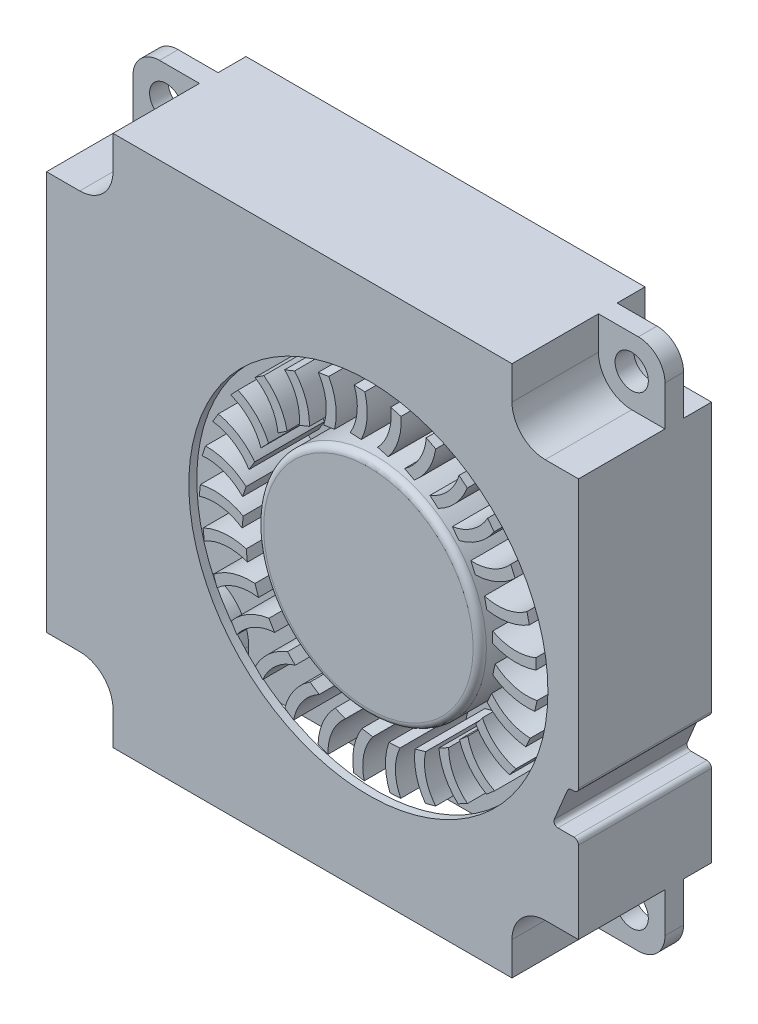
SolidWorks part; units mm, degrees
ref_plane "Front Plane" through (0, 0, 0) normal (0, 0, 1) x (1, 0, 0)
ref_plane "Top Plane" through (0, 0, 0) normal (0, 1, 0) x (1, 0, 0)
ref_plane "Right Plane" through (0, 0, 0) normal (1, 0, 0) x (0, 0, -1)
ref_plane "Plane3" through (0, 0, 25.289) normal (0, 0, 1) x (1, 0, 0)
sketch "Sketch35" plane through (0, 0, 25.289) normal (0, 0, 1) x (1, 0, 0)
  line L0 (41.5884, 7.4054) -> (41.5884, 47.4054)
  line L1 (41.5884, 47.4054) -> (1.5884, 47.4054)
  line L2 (1.5884, 47.4054) -> (1.5884, 7.4054)
  line L3 (1.5884, 7.4054) -> (41.5884, 7.4054)
extrude "Boss-Extrude31" add sketch "Sketch35" against normal blind 10 separate body
sketch "Sketch36" plane through (0, 7.4054, 0) normal (0, -1, 0) x (1, 0, 0)
  line L0 (35.5884, 24.689) -> (7.5884, 24.689)
  line L1 (7.5884, 24.689) -> (7.5884, 16.089)
  line L2 (7.5884, 16.089) -> (35.5884, 16.089)
  line L3 (35.5884, 16.089) -> (35.5884, 24.689)
extrude "Cut-Extrude1" cut sketch "Sketch36" against normal blind 39
ref_plane "Plane4" through (7.5884, 0, 0) normal (1, 0, 0) x (0, 0, -1)
sketch "Sketch41" plane through (7.5884, 0, 0) normal (1, 0, 0) x (0, 0, -1)
  line L0 (-24.689, 46.4054) -> (-24.689, 13.4054)
  line L1 (-24.689, 13.4054) -> (-16.089, 13.4054)
  line L2 (-16.089, 13.4054) -> (-16.089, 46.4054)
  line L3 (-16.089, 46.4054) -> (-24.689, 46.4054)
extrude "Cut-Extrude2" cut sketch "Sketch41" against normal blind 5
sketch "Sketch42" plane through (35.5884, 0, 0) normal (-1, 0, 0) x (0, 0, 1)
  line L0 (24.689, 13.4054) -> (24.689, 46.4054)
  line L1 (24.689, 46.4054) -> (16.089, 46.4054)
  line L2 (16.089, 46.4054) -> (16.089, 13.4054)
  line L3 (16.089, 13.4054) -> (24.689, 13.4054)
extrude "Cut-Extrude3" cut sketch "Sketch42" against normal blind 5
ref_plane "Plane5" through (0, 0, 24.689) normal (0, 0, -1) x (-1, 0, 0)
sketch "Sketch48" plane through (0, 0, 24.689) normal (0, 0, -1) x (-1, 0, 0)
  line L0 (-40.5884, 17.9054) -> (-40.5884, 22.825)
  line L1 (-39.8384, 22.1054) -> (-38.8384, 19.7054)
  line L2 (-40.0384, 17.9054) -> (-40.5884, 17.9054)
  arc A0 (-40.5884, 22.825) -> (-39.8384, 22.1054) centre (-41.0384, 21.6054) cw
  arc A1 (-38.8384, 19.7054) -> (-40.0384, 17.9054) centre (-40.0384, 19.2054) cw
extrude "Boss-Extrude32" add sketch "Sketch48" along normal blind 8.6
sketch "Sketch49" plane through (0, 0, 15.289) normal (0, 0, -1) x (-1, 0, 0)
  line L0 (-41.5884, 18.9054) -> (-40.0384, 18.9054)
  line L1 (-39.7615, 19.3207) -> (-40.8384, 21.9054)
  line L2 (-40.8384, 21.9054) -> (-41.5884, 21.9054)
  line L3 (-41.5884, 21.9054) -> (-41.5884, 18.9054)
  arc A0 (-40.0384, 18.9054) -> (-39.7615, 19.3207) centre (-40.0384, 19.2054) ccw
extrude "Cut-Extrude4" cut sketch "Sketch49" against normal through all
sketch "Sketch50" plane through (0, 0, 24.689) normal (0, 0, -1) x (-1, 0, 0)
  line L0 (-40.5884, 41.4054) -> (-40.5884, 46.4054)
  line L1 (-40.5884, 46.4054) -> (-35.5884, 46.4054)
  line L2 (-35.5884, 46.4054) -> (-35.5884, 41.4054)
  line L3 (-35.5884, 41.4054) -> (-40.5884, 41.4054)
extrude "Boss-Extrude33" add sketch "Sketch50" along normal blind 8.6
sketch "Sketch51" plane through (0, 0, 24.689) normal (0, 0, -1) x (-1, 0, 0)
  line L0 (-7.5884, 46.4054) -> (-2.5884, 46.4054)
  line L1 (-2.5884, 46.4054) -> (-2.5884, 41.4054)
  line L2 (-2.5884, 41.4054) -> (-7.5884, 41.4054)
  line L3 (-7.5884, 41.4054) -> (-7.5884, 46.4054)
extrude "Boss-Extrude34" add sketch "Sketch51" along normal blind 8.6
sketch "Sketch52" plane through (0, 0, 25.289) normal (0, 0, 1) x (1, 0, 0)
  line L0 (6.5884, 7.4054) -> (6.5884, 12.4054)
  line L1 (6.5884, 12.4054) -> (1.5884, 12.4054)
  line L2 (1.5884, 12.4054) -> (1.5884, 7.4054)
  line L3 (1.5884, 7.4054) -> (6.5884, 7.4054)
extrude "Cut-Extrude5" cut sketch "Sketch52" against normal blind 6.5
sketch "Sketch53" plane through (0, 0, 25.289) normal (0, 0, 1) x (1, 0, 0)
  line L0 (1.5884, 42.4054) -> (6.5884, 42.4054)
  line L1 (6.5884, 42.4054) -> (6.5884, 47.4054)
  line L2 (6.5884, 47.4054) -> (1.5884, 47.4054)
  line L3 (1.5884, 47.4054) -> (1.5884, 42.4054)
extrude "Cut-Extrude6" cut sketch "Sketch53" against normal blind 6.5
sketch "Sketch54" plane through (0, 0, 25.289) normal (0, 0, 1) x (1, 0, 0)
  line L0 (41.5884, 12.4054) -> (36.5884, 12.4054)
  line L1 (36.5884, 12.4054) -> (36.5884, 7.4054)
  line L2 (36.5884, 7.4054) -> (41.5884, 7.4054)
  line L3 (41.5884, 7.4054) -> (41.5884, 12.4054)
extrude "Cut-Extrude7" cut sketch "Sketch54" against normal blind 6.5
sketch "Sketch55" plane through (0, 0, 25.289) normal (0, 0, 1) x (1, 0, 0)
  line L0 (36.5884, 47.4054) -> (36.5884, 42.4054)
  line L1 (36.5884, 42.4054) -> (41.5884, 42.4054)
  line L2 (41.5884, 42.4054) -> (41.5884, 47.4054)
  line L3 (41.5884, 47.4054) -> (36.5884, 47.4054)
extrude "Cut-Extrude8" cut sketch "Sketch55" against normal blind 6.5
sketch "Sketch56" plane through (0, 0, 15.289) normal (0, 0, -1) x (-1, 0, 0)
  line L0 (-41.5884, 42.4054) -> (-36.5884, 42.4054)
  line L1 (-36.5884, 42.4054) -> (-36.5884, 47.4054)
  line L2 (-36.5884, 47.4054) -> (-41.5884, 47.4054)
  line L3 (-41.5884, 47.4054) -> (-41.5884, 42.4054)
extrude "Cut-Extrude9" cut sketch "Sketch56" against normal blind 2.1
sketch "Sketch57" plane through (0, 0, 15.289) normal (0, 0, -1) x (-1, 0, 0)
  line L0 (-36.5884, 7.4054) -> (-36.5884, 12.4054)
  line L1 (-36.5884, 12.4054) -> (-41.5884, 12.4054)
  line L2 (-41.5884, 12.4054) -> (-41.5884, 7.4054)
  line L3 (-41.5884, 7.4054) -> (-36.5884, 7.4054)
extrude "Cut-Extrude10" cut sketch "Sketch57" against normal blind 2.1
sketch "Sketch58" plane through (0, 0, 15.289) normal (0, 0, -1) x (-1, 0, 0)
  line L0 (-6.5884, 42.4054) -> (-1.5884, 42.4054)
  line L1 (-1.5884, 42.4054) -> (-1.5884, 47.4054)
  line L2 (-1.5884, 47.4054) -> (-6.5884, 47.4054)
  line L3 (-6.5884, 47.4054) -> (-6.5884, 42.4054)
extrude "Cut-Extrude11" cut sketch "Sketch58" against normal blind 2.1
sketch "Sketch59" plane through (0, 0, 15.289) normal (0, 0, -1) x (-1, 0, 0)
  line L0 (-6.5884, 12.4054) -> (-6.5884, 7.4054)
  line L1 (-6.5884, 7.4054) -> (-1.5884, 7.4054)
  line L2 (-1.5884, 7.4054) -> (-1.5884, 12.4054)
  line L3 (-1.5884, 12.4054) -> (-6.5884, 12.4054)
extrude "Cut-Extrude12" cut sketch "Sketch59" against normal blind 2.1
hole_wizard "Ø2.5 (2.5) Diameter Hole1" positions "Sketch61" profile "Sketch60" hole size "Ø2.5" standard "ANSI Metric"
sketch "Sketch61" plane through (0, 0, 18.789) normal (0, 0, 1) x (1, 0, 0)
  point P0 (4.0884, 44.9054)
  point P1 (39.0884, 9.9054)
sketch "Sketch60" plane through (4.0884, 44.9054, 18.789) normal (1, 0, 0) x (0, -1, 0)
  line L0 (0, 0) -> (0, 3.5)
  line L1 (0, 3.5) -> (1.25, 3.5)
  line L2 (1.25, 3.5) -> (1.25, 0)
  line L5 (1.25, 0) -> (0, 0)
  line L10 (0, 3.5) -> (-1.25, 3.5) construction
  line L11 (0, -6.35) -> (0, 107.95) construction
  dimension "Hole Dia." = 2.5
  dimension "Hole Depth" = 3.5
  dimension "Drill Angle" = 180
hole_wizard "M24 Clearance Hole1" positions "Sketch63" profile "Sketch62" hole size "M24" standard "ANSI Metric"
sketch "Sketch63" plane through (0, 0, 25.289) normal (0, 0, 1) x (1, 0, 0)
  point P0 (25.7884, 27.4054)
sketch "Sketch62" plane through (25.7884, 27.4054, 25.289) normal (1, 0, 0) x (0, -1, 0)
  line L0 (0, 0) -> (0, 0.6)
  line L1 (0, 0.6) -> (13.5, 0.6)
  line L2 (13.5, 0.6) -> (13.5, 0)
  line L5 (13.5, 0) -> (0, 0)
  line L11 (0, -6.35) -> (0, 107.95) construction
  dimension "Thru Hole Dia." = 27
  dimension "Thru Hole Depth" = 0.6
hole_wizard "Ø2.5 (2.5) Diameter Hole2" positions "Sketch65" profile "Sketch64" hole size "Ø2.5" standard "ANSI Metric"
sketch "Sketch65" plane through (0, 0, 17.389) normal (0, 0, -1) x (-1, 0, 0)
  point P0 (-4.0884, 9.9054)
  point P1 (-39.0884, 44.9054)
sketch "Sketch64" plane through (4.0884, 9.9054, 17.389) normal (1, 0, 0) x (0, 1, 0)
  line L0 (0, 0) -> (0, 7.9)
  line L1 (0, 7.9) -> (1.25, 7.9)
  line L2 (1.25, 7.9) -> (1.25, 0)
  line L5 (1.25, 0) -> (0, 0)
  line L10 (0, 7.9) -> (-1.25, 7.9) construction
  line L11 (0, -6.35) -> (0, 107.95) construction
  dimension "Hole Dia." = 2.5
  dimension "Hole Depth" = 7.9
  dimension "Drill Angle" = 180
fillet "Fillet2" radius 0.35 3 edges at (41.5884, 18.9054, 20.289) (40.8384, 21.9054, 20.289) (41.5884, 21.9054, 20.289)
fillet "Fillet3" radius 2 4 edges at (1.5884, 47.4054, 18.089) (41.5884, 47.4054, 18.089) (1.5884, 7.4054, 18.089) (41.5884, 7.4054, 18.089)
fillet "Fillet4" radius 2.5 8 edges at (6.5884, 12.4054, 22.039) (36.5884, 12.4054, 16.339) (36.5884, 42.4054, 16.339) (6.5884, 12.4054, 16.339) (6.5884, 42.4054, 16.339) (36.5884, 12.4054, 22.039) (6.5884, 42.4054, 22.039) (36.5884, 42.4054, 22.039)
fillet "Fillet5" radius 3.5 4 edges at (7.5884, 41.4054, 20.389) (7.5884, 13.4054, 20.389) (35.5884, 13.4054, 20.389) (35.5884, 41.4054, 20.389)
ref_plane "Plane6" through (0, 0, 20.039) normal (0, 0, 1) x (1, 0, 0)
sketch "Sketch72" plane through (0, 0, 20.039) normal (0, 0, 1) x (1, 0, 0)
  line L0 (28.2453, 39.8011) -> (27.4688, 40.0157)
  line L1 (25.5232, 40.0394) -> (24.7186, 40.0821)
  line L2 (22.8134, 39.687) -> (22.0185, 39.5558)
  line L3 (20.2428, 38.7604) -> (19.4946, 38.4613)
  line L4 (17.9314, 37.3028) -> (17.2651, 36.8499)
  line L5 (15.9875, 35.3824) -> (15.4341, 34.7968)
  line L6 (14.5018, 33.089) -> (14.0872, 32.3981)
  line L7 (13.5439, 30.5298) -> (13.2875, 29.766)
  line L8 (13.1585, 27.8245) -> (13.0723, 27.0235)
  line L9 (13.3636, 25.0997) -> (13.4517, 24.2988)
  line L10 (14.1498, 22.4826) -> (14.4079, 21.7194)
  line L11 (15.4801, 20.0958) -> (15.8963, 19.4059)
  line L12 (17.2925, 18.0507) -> (17.8472, 17.4664)
  line L13 (19.5021, 16.443) -> (20.1694, 15.9916)
  line L14 (22.0056, 15.3479) -> (22.7544, 15.0506)
  line L15 (24.686, 14.8167) -> (25.4813, 14.6872)
  line L16 (27.418, 14.874) -> (28.2225, 14.9185)
  line L17 (30.0738, 15.5173) -> (30.8499, 15.7337)
  line L18 (32.5292, 16.7165) -> (33.2406, 17.0947)
  line L19 (34.6694, 18.4154) -> (35.2828, 18.9377)
  line L20 (36.3943, 20.5348) -> (36.8812, 21.1767)
  line L21 (37.6233, 22.9754) -> (37.9608, 23.707)
  line L22 (38.2989, 25.6231) -> (38.4712, 26.4102)
  line L23 (38.3896, 28.3542) -> (38.3887, 29.1599)
  line L24 (37.891, 31.0409) -> (37.7169, 31.8275)
  line L25 (36.8265, 33.5576) -> (36.4874, 34.2884)
  line L26 (35.2459, 35.7866) -> (34.7576, 36.4275)
  line L27 (33.2231, 37.6237) -> (32.6084, 38.1447)
  line L28 (30.8526, 38.9831) -> (30.1403, 39.3597)
  arc A0 (29.3247, 37.2919) -> (27.8844, 37.694) centre (25.7884, 27.4054) ccw
  arc A1 (27.8844, 37.694) -> (28.2453, 39.8011) centre (23.7564, 39.4856) ccw
  arc A2 (27.4688, 40.0157) -> (27.1167, 37.821) centre (23.7564, 39.4856) cw
  arc A3 (27.1167, 37.821) -> (25.6236, 37.9041) centre (25.7884, 27.4054) ccw
  arc A4 (25.6236, 37.9041) -> (25.5232, 40.0394) centre (21.207, 38.7664) ccw
  arc A5 (24.7186, 40.0821) -> (24.8466, 37.863) centre (21.207, 38.7664) cw
  arc A6 (24.8466, 37.863) -> (23.3705, 37.6232) centre (25.7884, 27.4054) ccw
  arc A7 (23.3705, 37.6232) -> (22.8134, 39.687) centre (18.8718, 37.5159) ccw
  arc A8 (22.0185, 39.5558) -> (22.6205, 37.4161) centre (18.8718, 37.5159) cw
  arc A9 (22.6205, 37.4161) -> (21.2305, 36.8645) centre (25.7884, 27.4054) ccw
  arc A10 (21.2305, 36.8645) -> (20.2428, 38.7604) centre (16.8601, 35.7927) ccw
  arc A11 (19.4946, 38.4613) -> (20.5425, 36.501) centre (16.8601, 35.7927) cw
  arc A12 (20.5425, 36.501) -> (19.3037, 35.6636) centre (25.7884, 27.4054) ccw
  arc A13 (19.3037, 35.6636) -> (17.9314, 37.3028) centre (15.2658, 33.6773) ccw
  arc A14 (17.2651, 36.8499) -> (18.7099, 35.1607) centre (15.2658, 33.6773) cw
  arc A15 (18.7099, 35.1607) -> (17.68, 34.0765) centre (25.7884, 27.4054) ccw
  arc A16 (17.68, 34.0765) -> (15.9875, 35.3824) centre (14.1635, 31.2686) ccw
  arc A17 (15.4341, 34.7968) -> (17.2082, 33.4577) centre (14.1635, 31.2686) cw
  arc A18 (17.2082, 33.4577) -> (16.4355, 32.1775) centre (25.7884, 27.4054) ccw
  arc A19 (16.4355, 32.1775) -> (14.5018, 33.089) centre (13.6048, 28.6793) ccw
  arc A20 (14.0872, 32.3981) -> (16.1077, 31.4717) centre (13.6048, 28.6793) cw
  arc A21 (16.1077, 31.4717) -> (15.6283, 30.0553) centre (25.7884, 27.4054) ccw
  arc A22 (15.6283, 30.0553) -> (13.5439, 30.5298) centre (13.6158, 26.0304) ccw
  arc A23 (13.2875, 29.766) -> (15.4599, 29.2956) centre (13.6158, 26.0304) cw
  arc A24 (15.4599, 29.2956) -> (15.2961, 27.8092) centre (25.7884, 27.4054) ccw
  arc A25 (15.2961, 27.8092) -> (13.1585, 27.8245) centre (14.196, 23.4458) ccw
  arc A26 (13.0723, 27.0235) -> (15.295, 27.0311) centre (14.196, 23.4458) cw
  arc A27 (15.295, 27.0311) -> (15.4546, 25.5443) centre (25.7884, 27.4054) ccw
  arc A28 (15.4546, 25.5443) -> (13.3636, 25.0997) centre (15.3182, 21.0463) ccw
  arc A29 (13.4517, 24.2988) -> (15.6208, 24.7841) centre (15.3182, 21.0463) cw
  arc A30 (15.6208, 24.7841) -> (16.0963, 23.3663) centre (25.7884, 27.4054) ccw
  arc A31 (16.0963, 23.3663) -> (14.1498, 22.4826) centre (16.93, 18.9442) ccw
  arc A32 (14.4079, 21.7194) -> (16.422, 22.6596) centre (16.93, 18.9442) cw
  arc A33 (16.422, 22.6596) -> (17.1912, 21.3772) centre (25.7884, 27.4054) ccw
  arc A34 (17.1912, 21.3772) -> (15.4801, 20.0958) centre (18.956, 17.2377) ccw
  arc A35 (15.8963, 19.4059) -> (17.6612, 20.7571) centre (18.956, 17.2377) cw
  arc A36 (17.6612, 20.7571) -> (18.688, 19.67) centre (25.7884, 27.4054) ccw
  arc A37 (18.688, 19.67) -> (17.2925, 18.0507) centre (21.3014, 16.0067) ccw
  arc A38 (17.8472, 17.4664) -> (19.2804, 19.1654) centre (21.3014, 16.0067) cw
  arc A39 (19.2804, 19.1654) -> (20.5169, 18.3245) centre (25.7884, 27.4054) ccw
  arc A40 (20.5169, 18.3245) -> (19.5021, 16.443) centre (23.8567, 15.3086) ccw
  arc A41 (20.1694, 15.9916) -> (21.2039, 17.9591) centre (23.8567, 15.3086) cw
  arc A42 (21.2039, 17.9591) -> (22.5923, 17.4036) centre (25.7884, 27.4054) ccw
  arc A43 (22.5923, 17.4036) -> (22.0056, 15.3479) centre (26.5023, 15.1762) ccw
  arc A44 (22.7544, 15.0506) -> (23.3417, 17.1944) centre (26.5023, 15.1762) cw
  arc A45 (23.3417, 17.1944) -> (24.8171, 16.9504) centre (25.7884, 27.4054) ccw
  arc A46 (24.8171, 16.9504) -> (24.686, 14.8167) centre (29.1145, 15.6156) ccw
  arc A47 (25.4813, 14.6872) -> (25.594, 16.9072) centre (29.1145, 15.6156) cw
  arc A48 (25.594, 16.9072) -> (27.0873, 16.986) centre (25.7884, 27.4054) ccw
  arc A49 (27.0873, 16.986) -> (27.418, 14.874) centre (31.5712, 16.6062) ccw
  arc A50 (28.2225, 14.9185) -> (27.8553, 17.1108) centre (31.5712, 16.6062) cw
  arc A51 (27.8553, 17.1108) -> (29.2968, 17.5088) centre (25.7884, 27.4054) ccw
  arc A52 (29.2968, 17.5088) -> (30.0738, 15.5173) centre (33.7575, 18.1019) ccw
  arc A53 (30.8499, 15.7337) -> (30.02, 17.7958) centre (33.7575, 18.1019) cw
  arc A54 (30.02, 17.7958) -> (31.3422, 18.4944) centre (25.7884, 27.4054) ccw
  arc A55 (31.3422, 18.4944) -> (32.5292, 16.7165) centre (35.5712, 20.0325) ccw
  arc A56 (33.2406, 17.0947) -> (31.9869, 18.9302) centre (35.5712, 20.0325) cw
  arc A57 (31.9869, 18.9302) -> (33.128, 19.8967) centre (25.7884, 27.4054) ccw
  arc A58 (33.128, 19.8967) -> (34.6694, 18.4154) centre (36.9274, 22.3079) ccw
  arc A59 (35.2828, 18.9377) -> (33.6639, 20.4608) centre (36.9274, 22.3079) cw
  arc A60 (33.6639, 20.4608) -> (34.5705, 21.65) centre (25.7884, 27.4054) ccw
  arc A61 (34.5705, 21.65) -> (36.3943, 20.5348) centre (37.7628, 24.8216) ccw
  arc A62 (36.8812, 21.1767) -> (34.9726, 22.3162) centre (37.7628, 24.8216) cw
  arc A63 (34.9726, 22.3162) -> (35.6024, 23.6724) centre (25.7884, 27.4054) ccw
  arc A64 (35.6024, 23.6724) -> (37.6233, 22.9754) centre (38.0383, 27.4562) ccw
  arc A65 (37.9608, 23.707) -> (35.8519, 24.4095) centre (38.0383, 27.4562) cw
  arc A66 (35.8519, 24.4095) -> (36.1754, 25.8695) centre (25.7884, 27.4054) ccw
  arc A67 (36.1754, 25.8695) -> (38.2989, 25.6231) centre (37.7409, 30.0884) ccw
  arc A68 (38.4712, 26.4102) -> (36.2607, 26.6429) centre (37.7409, 30.0884) cw
  arc A69 (36.2607, 26.6429) -> (36.2628, 28.1383) centre (25.7884, 27.4054) ccw
  arc A70 (36.2628, 28.1383) -> (38.3896, 28.3542) centre (36.8847, 32.5951) ccw
  arc A71 (38.3887, 29.1599) -> (36.1797, 28.9119) centre (36.8847, 32.5951) cw
  arc A72 (36.1797, 28.9119) -> (35.8603, 30.3728) centre (25.7884, 27.4054) ccw
  arc A73 (35.8603, 30.3728) -> (37.891, 31.0409) centre (35.5097, 34.8591) ccw
  arc A74 (37.7169, 31.8275) -> (35.6129, 31.1106) centre (35.5097, 34.8591) cw
  arc A75 (35.6129, 31.1106) -> (34.9869, 32.4686) centre (25.7884, 27.4054) ccw
  arc A76 (34.9869, 32.4686) -> (36.8265, 33.5576) centre (33.6801, 36.7747) ccw
  arc A77 (36.4874, 34.2884) -> (34.5867, 33.1359) centre (33.6801, 36.7747) cw
  arc A78 (34.5867, 33.1359) -> (33.6834, 34.3277) centre (25.7884, 27.4054) ccw
  arc A79 (33.6834, 34.3277) -> (35.2459, 35.7866) centre (31.4814, 38.2521) ccw
  arc A80 (34.7576, 36.4275) -> (33.1491, 34.8933) centre (31.4814, 38.2521) cw
  arc A81 (33.1491, 34.8933) -> (32.0108, 35.863) centre (25.7884, 27.4054) ccw
  arc A82 (32.0108, 35.863) -> (33.2231, 37.6237) centre (29.0166, 39.2223) ccw
  arc A83 (32.6084, 38.1447) -> (31.3673, 36.3006) centre (29.0166, 39.2223) cw
  arc A84 (31.3673, 36.3006) -> (30.0471, 37.0029) centre (25.7884, 27.4054) ccw
  arc A85 (30.0471, 37.0029) -> (30.8526, 38.9831) centre (26.4008, 39.64) ccw
  arc A86 (30.1403, 39.3597) -> (29.3247, 37.2919) centre (26.4008, 39.64) cw
extrude "Boss-Extrude35" add sketch "Sketch72" against normal blind 2 separate body
sketch "Sketch80" plane through (0, 0, 20.039) normal (0, 0, 1) x (1, 0, 0)
  line L0 (27.4688, 40.0157) -> (28.2453, 39.8011)
  line L1 (27.2861, 36.6943) -> (26.4869, 36.9153)
  arc A0 (26.4869, 36.9153) -> (27.4688, 40.0157) centre (23.7564, 39.4856) ccw
  arc A1 (28.2453, 39.8011) -> (27.2861, 36.6943) centre (23.7564, 39.4856) cw
extrude "Boss-Extrude36" add sketch "Sketch80" along normal blind 5.25
sketch "Sketch81" plane through (0, 0, 20.039) normal (0, 0, 1) x (1, 0, 0)
  line L0 (30.1403, 39.3597) -> (30.8526, 38.9831)
  line L1 (29.2479, 36.1552) -> (28.5149, 36.5428)
  arc A0 (28.5149, 36.5428) -> (30.1403, 39.3597) centre (26.4008, 39.64) ccw
  arc A1 (30.8526, 38.9831) -> (29.2479, 36.1552) centre (26.4008, 39.64) cw
extrude "Boss-Extrude37" add sketch "Sketch81" along normal blind 5.25
sketch "Sketch82" plane through (0, 0, 20.039) normal (0, 0, 1) x (1, 0, 0)
  line L0 (32.6084, 38.1447) -> (33.2231, 37.6237)
  line L1 (31.048, 35.2069) -> (30.4154, 35.743)
  arc A0 (30.4154, 35.743) -> (32.6084, 38.1447) centre (29.0166, 39.2223) ccw
  arc A1 (33.2231, 37.6237) -> (31.048, 35.2069) centre (29.0166, 39.2223) cw
extrude "Boss-Extrude38" add sketch "Sketch82" along normal blind 5.25
sketch "Sketch83" plane through (0, 0, 20.039) normal (0, 0, 1) x (1, 0, 0)
  line L0 (34.7576, 36.4275) -> (35.2459, 35.7866)
  line L1 (32.6022, 33.8939) -> (32.0996, 34.5534)
  arc A0 (32.0996, 34.5534) -> (34.7576, 36.4275) centre (31.4814, 38.2521) ccw
  arc A1 (35.2459, 35.7866) -> (32.6022, 33.8939) centre (31.4814, 38.2521) cw
extrude "Boss-Extrude39" add sketch "Sketch83" along normal blind 5.25
sketch "Sketch84" plane through (0, 0, 20.039) normal (0, 0, 1) x (1, 0, 0)
  line L0 (36.4874, 34.2884) -> (36.8265, 33.5576)
  line L1 (33.8377, 32.2774) -> (33.4887, 33.0295)
  arc A0 (33.4887, 33.0295) -> (36.4874, 34.2884) centre (33.6801, 36.7747) ccw
  arc A1 (36.8265, 33.5576) -> (33.8377, 32.2774) centre (33.6801, 36.7747) cw
extrude "Boss-Extrude40" add sketch "Sketch84" along normal blind 5.25
sketch "Sketch85" plane through (0, 0, 20.039) normal (0, 0, 1) x (1, 0, 0)
  line L0 (37.7169, 31.8275) -> (37.891, 31.0409)
  line L1 (34.6969, 30.4332) -> (34.5177, 31.2427)
  arc A0 (34.5177, 31.2427) -> (37.7169, 31.8275) centre (35.5097, 34.8591) ccw
  arc A1 (37.891, 31.0409) -> (34.6969, 30.4332) centre (35.5097, 34.8591) cw
extrude "Boss-Extrude41" add sketch "Sketch85" along normal blind 5.25
sketch "Sketch86" plane through (0, 0, 20.039) normal (0, 0, 1) x (1, 0, 0)
  line L0 (38.3887, 29.1599) -> (38.3896, 28.3542)
  line L1 (35.1395, 28.4473) -> (35.1385, 29.2765)
  arc A0 (35.1385, 29.2765) -> (38.3887, 29.1599) centre (36.8847, 32.5951) ccw
  arc A1 (38.3896, 28.3542) -> (35.1395, 28.4473) centre (36.8847, 32.5951) cw
extrude "Boss-Extrude42" add sketch "Sketch86" along normal blind 5.25
sketch "Sketch87" plane through (0, 0, 20.039) normal (0, 0, 1) x (1, 0, 0)
  line L0 (38.4712, 26.4102) -> (38.2989, 25.6231)
  line L1 (35.1448, 26.4127) -> (35.3222, 27.2227)
  arc A0 (35.3222, 27.2227) -> (38.4712, 26.4102) centre (37.7409, 30.0884) ccw
  arc A1 (38.2989, 25.6231) -> (35.1448, 26.4127) centre (37.7409, 30.0884) cw
extrude "Boss-Extrude43" add sketch "Sketch87" along normal blind 5.25
sketch "Sketch88" plane through (0, 0, 20.039) normal (0, 0, 1) x (1, 0, 0)
  line L0 (37.9608, 23.707) -> (37.6233, 22.9754)
  line L1 (34.7127, 24.4246) -> (35.06, 25.1775)
  arc A0 (35.06, 25.1775) -> (37.9608, 23.707) centre (38.0383, 27.4562) ccw
  arc A1 (37.6233, 22.9754) -> (34.7127, 24.4246) centre (38.0383, 27.4562) cw
extrude "Boss-Extrude44" add sketch "Sketch88" along normal blind 5.25
sketch "Sketch89" plane through (0, 0, 20.039) normal (0, 0, 1) x (1, 0, 0)
  line L0 (36.8812, 21.1767) -> (36.3943, 20.5348)
  line L1 (33.8633, 22.5758) -> (34.3643, 23.2365)
  arc A0 (34.3643, 23.2365) -> (36.8812, 21.1767) centre (37.7628, 24.8216) ccw
  arc A1 (36.3943, 20.5348) -> (33.8633, 22.5758) centre (37.7628, 24.8216) cw
extrude "Boss-Extrude45" add sketch "Sketch89" along normal blind 5.25
sketch "Sketch90" plane through (0, 0, 20.039) normal (0, 0, 1) x (1, 0, 0)
  line L0 (35.2828, 18.9377) -> (34.6694, 18.4154)
  line L1 (32.6363, 20.9529) -> (33.2676, 21.4904)
  arc A0 (33.2676, 21.4904) -> (35.2828, 18.9377) centre (36.9274, 22.3079) ccw
  arc A1 (34.6694, 18.4154) -> (32.6363, 20.9529) centre (36.9274, 22.3079) cw
extrude "Boss-Extrude46" add sketch "Sketch90" along normal blind 5.25
sketch "Sketch91" plane through (0, 0, 20.039) normal (0, 0, 1) x (1, 0, 0)
  line L0 (33.2406, 17.0947) -> (32.5292, 16.7165)
  line L1 (31.0891, 19.6316) -> (31.8212, 20.0208)
  arc A0 (31.8212, 20.0208) -> (33.2406, 17.0947) centre (35.5712, 20.0325) ccw
  arc A1 (32.5292, 16.7165) -> (31.0891, 19.6316) centre (35.5712, 20.0325) cw
extrude "Boss-Extrude47" add sketch "Sketch91" along normal blind 5.25
sketch "Sketch92" plane through (0, 0, 20.039) normal (0, 0, 1) x (1, 0, 0)
  line L0 (30.8499, 15.7337) -> (30.0738, 15.5173)
  line L1 (29.294, 18.6739) -> (30.0927, 18.8966)
  arc A0 (30.0927, 18.8966) -> (30.8499, 15.7337) centre (33.7575, 18.1019) ccw
  arc A1 (30.0738, 15.5173) -> (29.294, 18.6739) centre (33.7575, 18.1019) cw
extrude "Boss-Extrude48" add sketch "Sketch92" along normal blind 5.25
sketch "Sketch93" plane through (0, 0, 20.039) normal (0, 0, 1) x (1, 0, 0)
  line L0 (28.2225, 14.9185) -> (27.418, 14.874)
  line L1 (27.3351, 18.1244) -> (28.1629, 18.1702)
  arc A0 (28.1629, 18.1702) -> (28.2225, 14.9185) centre (31.5712, 16.6062) ccw
  arc A1 (27.418, 14.874) -> (27.3351, 18.1244) centre (31.5712, 16.6062) cw
extrude "Boss-Extrude49" add sketch "Sketch93" along normal blind 5.25
sketch "Sketch94" plane through (0, 0, 20.039) normal (0, 0, 1) x (1, 0, 0)
  line L0 (25.4813, 14.6872) -> (24.686, 14.8167)
  line L1 (25.3038, 18.0089) -> (26.1222, 17.8757)
  arc A0 (26.1222, 17.8757) -> (25.4813, 14.6872) centre (29.1145, 15.6156) ccw
  arc A1 (24.686, 14.8167) -> (25.3038, 18.0089) centre (29.1145, 15.6156) cw
extrude "Boss-Extrude50" add sketch "Sketch94" along normal blind 5.25
sketch "Sketch95" plane through (0, 0, 20.039) normal (0, 0, 1) x (1, 0, 0)
  line L0 (22.7544, 15.0506) -> (22.0056, 15.3479)
  line L1 (23.2951, 18.3327) -> (24.0657, 18.0267)
  arc A0 (24.0657, 18.0267) -> (22.7544, 15.0506) centre (26.5023, 15.1762) ccw
  arc A1 (22.0056, 15.3479) -> (23.2951, 18.3327) centre (26.5023, 15.1762) cw
extrude "Boss-Extrude51" add sketch "Sketch95" along normal blind 5.25
sketch "Sketch96" plane through (0, 0, 20.039) normal (0, 0, 1) x (1, 0, 0)
  line L0 (20.1694, 15.9916) -> (19.5021, 16.443)
  line L1 (21.4031, 19.0808) -> (22.0899, 18.6163)
  arc A0 (22.0899, 18.6163) -> (20.1694, 15.9916) centre (23.8567, 15.3086) ccw
  arc A1 (19.5021, 16.443) -> (21.4031, 19.0808) centre (23.8567, 15.3086) cw
extrude "Boss-Extrude52" add sketch "Sketch96" along normal blind 5.25
sketch "Sketch97" plane through (0, 0, 20.039) normal (0, 0, 1) x (1, 0, 0)
  line L0 (17.8472, 17.4664) -> (17.2925, 18.0507)
  line L1 (19.7161, 20.2182) -> (20.287, 19.6168)
  arc A0 (20.287, 19.6168) -> (17.8472, 17.4664) centre (21.3014, 16.0067) ccw
  arc A1 (17.2925, 18.0507) -> (19.7161, 20.2182) centre (21.3014, 16.0067) cw
extrude "Boss-Extrude53" add sketch "Sketch97" along normal blind 5.25
sketch "Sketch98" plane through (0, 0, 20.039) normal (0, 0, 1) x (1, 0, 0)
  line L0 (15.8963, 19.4059) -> (15.4801, 20.0958)
  line L1 (18.313, 21.6916) -> (18.7413, 20.9816)
  arc A0 (18.7413, 20.9816) -> (15.8963, 19.4059) centre (18.956, 17.2377) ccw
  arc A1 (15.4801, 20.0958) -> (18.313, 21.6916) centre (18.956, 17.2377) cw
extrude "Boss-Extrude54" add sketch "Sketch98" along normal blind 5.25
sketch "Sketch99" plane through (0, 0, 20.039) normal (0, 0, 1) x (1, 0, 0)
  line L0 (14.4079, 21.7194) -> (14.1498, 22.4826)
  line L1 (17.2595, 23.4321) -> (17.5251, 22.6467)
  arc A0 (17.5251, 22.6467) -> (14.4079, 21.7194) centre (16.93, 18.9442) ccw
  arc A1 (14.1498, 22.4826) -> (17.2595, 23.4321) centre (16.93, 18.9442) cw
extrude "Boss-Extrude55" add sketch "Sketch99" along normal blind 5.25
sketch "Sketch100" plane through (0, 0, 20.039) normal (0, 0, 1) x (1, 0, 0)
  line L0 (13.4517, 24.2988) -> (13.3636, 25.0997)
  line L1 (16.6048, 25.3585) -> (16.6953, 24.5343)
  arc A0 (16.6953, 24.5343) -> (13.4517, 24.2988) centre (15.3182, 21.0463) ccw
  arc A1 (13.3636, 25.0997) -> (16.6048, 25.3585) centre (15.3182, 21.0463) cw
extrude "Boss-Extrude56" add sketch "Sketch100" along normal blind 5.25
sketch "Sketch101" plane through (0, 0, 20.039) normal (0, 0, 1) x (1, 0, 0)
  line L0 (13.0723, 27.0235) -> (13.1585, 27.8245)
  line L1 (16.3794, 27.3805) -> (16.2907, 26.5561)
  arc A0 (16.2907, 26.5561) -> (13.0723, 27.0235) centre (14.196, 23.4458) ccw
  arc A1 (13.1585, 27.8245) -> (16.3794, 27.3805) centre (14.196, 23.4458) cw
extrude "Boss-Extrude57" add sketch "Sketch101" along normal blind 5.25
sketch "Sketch102" plane through (0, 0, 20.039) normal (0, 0, 1) x (1, 0, 0)
  line L0 (13.2875, 29.766) -> (13.5439, 30.5298)
  line L1 (16.5941, 29.4038) -> (16.3302, 28.6177)
  arc A0 (16.3302, 28.6177) -> (13.2875, 29.766) centre (13.6158, 26.0304) ccw
  arc A1 (13.5439, 30.5298) -> (16.5941, 29.4038) centre (13.6158, 26.0304) cw
extrude "Boss-Extrude58" add sketch "Sketch102" along normal blind 5.25
sketch "Sketch103" plane through (0, 0, 20.039) normal (0, 0, 1) x (1, 0, 0)
  line L0 (14.0872, 32.3981) -> (14.5018, 33.089)
  line L1 (17.2386, 31.3335) -> (16.812, 30.6226)
  arc A0 (16.812, 30.6226) -> (14.0872, 32.3981) centre (13.6048, 28.6793) ccw
  arc A1 (14.5018, 33.089) -> (17.2386, 31.3335) centre (13.6048, 28.6793) cw
extrude "Boss-Extrude59" add sketch "Sketch103" along normal blind 5.25
sketch "Sketch104" plane through (0, 0, 20.039) normal (0, 0, 1) x (1, 0, 0)
  line L0 (15.4341, 34.7968) -> (15.9875, 35.3824)
  line L1 (18.283, 33.0796) -> (17.7135, 32.477)
  arc A0 (17.7135, 32.477) -> (15.4341, 34.7968) centre (14.1635, 31.2686) ccw
  arc A1 (15.9875, 35.3824) -> (18.283, 33.0796) centre (14.1635, 31.2686) cw
extrude "Boss-Extrude60" add sketch "Sketch104" along normal blind 5.25
sketch "Sketch105" plane through (0, 0, 20.039) normal (0, 0, 1) x (1, 0, 0)
  line L0 (17.2651, 36.8499) -> (17.9314, 37.3028)
  line L1 (19.6783, 34.5604) -> (18.9925, 34.0943)
  arc A0 (18.9925, 34.0943) -> (17.2651, 36.8499) centre (15.2658, 33.6773) ccw
  arc A1 (17.9314, 37.3028) -> (19.6783, 34.5604) centre (15.2658, 33.6773) cw
extrude "Boss-Extrude61" add sketch "Sketch105" along normal blind 5.25
sketch "Sketch106" plane through (0, 0, 20.039) normal (0, 0, 1) x (1, 0, 0)
  line L0 (19.4946, 38.4613) -> (20.2428, 38.7604)
  line L1 (21.3592, 35.7066) -> (20.5893, 35.3988)
  arc A0 (20.5893, 35.3988) -> (19.4946, 38.4613) centre (16.8601, 35.7927) ccw
  arc A1 (20.2428, 38.7604) -> (21.3592, 35.7066) centre (16.8601, 35.7927) cw
extrude "Boss-Extrude62" add sketch "Sketch106" along normal blind 5.25
sketch "Sketch107" plane through (0, 0, 20.039) normal (0, 0, 1) x (1, 0, 0)
  line L0 (24.7186, 40.0821) -> (25.5232, 40.0394)
  line L1 (25.2542, 36.7991) -> (24.4262, 36.8431)
  arc A0 (24.4262, 36.8431) -> (24.7186, 40.0821) centre (21.207, 38.7664) ccw
  arc A1 (25.5232, 40.0394) -> (25.2542, 36.7991) centre (21.207, 38.7664) cw
extrude "Boss-Extrude63" add sketch "Sketch107" along normal blind 5.25
sketch "Sketch108" plane through (0, 0, 20.039) normal (0, 0, 1) x (1, 0, 0)
  line L0 (22.0185, 39.5558) -> (22.8134, 39.687)
  line L1 (23.2473, 36.4647) -> (22.4292, 36.3296)
  arc A0 (22.4292, 36.3296) -> (22.0185, 39.5558) centre (18.8718, 37.5159) ccw
  arc A1 (22.8134, 39.687) -> (23.2473, 36.4647) centre (18.8718, 37.5159) cw
extrude "Boss-Extrude64" add sketch "Sketch108" along normal blind 5.25
ref_plane "Plane7" through (0, 27.4054, 0) normal (0, -1, 0) x (-1, 0, 0)
sketch "Sketch116" plane through (0, 27.4054, 0) normal (0, -1, 0) x (-1, 0, 0)
  line L0 (-34.1634, -25.289) -> (-25.7884, -25.289)
  line L1 (-25.7884, -25.289) -> (-25.7884, -20.039)
  line L2 (-25.7884, -20.039) -> (-34.1634, -20.039)
  line L3 (-34.1634, -20.039) -> (-34.1634, -25.289)
  line L4 (-25.7884, -25.289) -> (-25.7884, -20.039) construction
revolve "Revolve2" add sketch "Sketch116" angle 360 about L4
fillet "Fillet6" radius 0.5 1 edges at (17.4134, 27.4054, 25.289)
